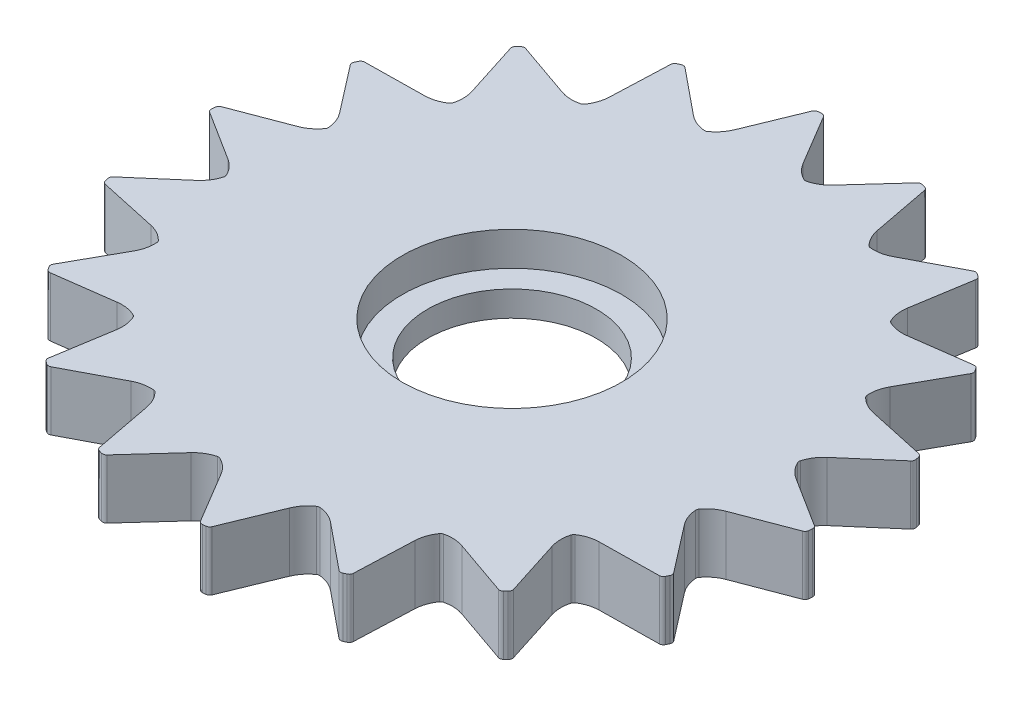
SolidWorks part; units mm, degrees
material "ASTM A36 Steel"
ref_plane "Front Plane" through (0, 0, 0) normal (0, 0, 1) x (1, 0, 0)
ref_plane "Top Plane" through (0, 0, 0) normal (0, 1, 0) x (1, 0, 0)
ref_plane "Right Plane" through (0, 0, 0) normal (1, 0, 0) x (0, 0, -1)
sketch "Sketch1" plane through (0, 0, 0) normal (0, 1, 0) x (1, 0, 0)
  line L0 (381.3467, 381.3133) -> (386.6619, 385.9057)
  line L1 (380.5553, 394.9141) -> (387.1206, 397.4117)
  line L2 (388.2042, 401.2572) -> (383.9089, 406.8152)
  line L3 (384.4633, 407.9654) -> (391.487, 408.0669)
  line L4 (393.8205, 411.3099) -> (391.6851, 418.0018)
  line L5 (392.5995, 418.893) -> (399.2343, 416.5861)
  line L6 (402.5362, 418.8354) -> (402.8184, 425.8541)
  line L7 (403.9825, 426.3788) -> (409.4282, 421.9419)
  line L8 (413.3003, 422.9262) -> (415.966, 429.4251)
  line L9 (417.2393, 429.52) -> (420.839, 423.4881)
  line L10 (424.8142, 423.0887) -> (429.5419, 428.2839)
  line L11 (430.7709, 427.9376) -> (432.0905, 421.0383)
  line L12 (435.6894, 419.3034) -> (441.9089, 422.5684)
  line L13 (442.9453, 421.8226) -> (441.8256, 414.888)
  line L14 (444.6141, 412.0268) -> (451.5752, 412.9677)
  line L15 (452.2941, 411.9125) -> (448.8701, 405.779)
  line L16 (450.5119, 402.1367) -> (457.3749, 400.64)
  line L17 (457.6895, 399.4025) -> (452.3743, 394.8101)
  line L18 (452.6713, 390.8259) -> (458.6086, 387.0721)
  line L19 (458.4809, 385.8017) -> (451.9156, 383.3041)
  line L20 (450.832, 379.4586) -> (455.1273, 373.9006)
  line L21 (454.5729, 372.7504) -> (447.5492, 372.6489)
  line L22 (445.2157, 369.4059) -> (447.3511, 362.714)
  line L23 (446.4367, 361.8228) -> (439.8019, 364.1297)
  line L24 (436.5, 361.8804) -> (436.2178, 354.8617)
  line L25 (435.0537, 354.337) -> (429.608, 358.774)
  line L26 (425.736, 357.7896) -> (423.0702, 351.2907)
  line L27 (421.7969, 351.1958) -> (418.1972, 357.2277)
  line L28 (414.222, 357.6271) -> (409.4943, 352.4319)
  line L29 (408.2653, 352.7782) -> (406.9457, 359.6775)
  line L30 (403.3468, 361.4124) -> (397.1273, 358.1474)
  line L31 (396.0909, 358.8932) -> (397.2106, 365.8278)
  line L32 (394.4221, 368.689) -> (387.461, 367.7481)
  line L33 (386.7421, 368.8033) -> (390.1661, 374.9368)
  line L34 (386.3649, 389.8899) -> (380.4276, 393.6437)
  line L35 (388.5244, 378.5791) -> (381.6613, 380.0758)
  arc A0 (390.5213, 377.4784) -> (388.5244, 378.5791) centre (387.6721, 374.6709) ccw
  arc A1 (381.2838, 380.4387) -> (381.6613, 380.0758) centre (381.7678, 380.5643) ccw
  arc A2 (381.1884, 380.8141) -> (381.2838, 380.4387) centre (419.5181, 390.3579) ccw
  arc A3 (381.3467, 381.3133) -> (381.1884, 380.8141) centre (381.6736, 380.9349) ccw
  arc A4 (386.6619, 385.9057) -> (387.8908, 387.8264) centre (384.0467, 388.9325) ccw
  arc A5 (387.8908, 387.8264) -> (387.865, 388.1726) centre (387.4103, 387.9647) ccw
  arc A6 (380.1971, 394.1138) -> (380.4276, 393.6437) centre (380.6948, 394.0663) ccw
  arc A7 (380.2358, 394.4992) -> (380.1971, 394.1138) centre (419.5181, 390.3579) ccw
  arc A8 (380.5553, 394.9141) -> (380.2358, 394.4992) centre (380.733, 394.4468) ccw
  arc A9 (387.1206, 397.4117) -> (388.9323, 398.7963) centre (385.6984, 401.1503) ccw
  arc A10 (388.9323, 398.7963) -> (389.0265, 399.1304) centre (388.5281, 399.0905) ccw
  arc A11 (389.0265, 399.1304) -> (388.2042, 401.2572) centre (385.0393, 398.8112) ccw
  arc A12 (383.853, 407.3359) -> (383.9089, 406.8152) centre (384.3045, 407.121) ccw
  arc A13 (384.0212, 407.6848) -> (383.853, 407.3359) centre (419.5181, 390.3579) ccw
  arc A14 (384.4633, 407.9654) -> (384.0212, 407.6848) centre (384.4706, 407.4655) ccw
  arc A15 (391.487, 408.0669) -> (393.663, 408.7483) centre (391.4292, 412.0665) ccw
  arc A16 (393.663, 408.7483) -> (393.8657, 409.0301) centre (393.3838, 409.1631) ccw
  arc A17 (393.8657, 409.0301) -> (393.8205, 411.3099) centre (390.0098, 410.0939) ccw
  arc A18 (391.8107, 418.5102) -> (391.6851, 418.0018) centre (392.1614, 418.1538) ccw
  arc A19 (392.0881, 418.7805) -> (391.8107, 418.5102) centre (419.5181, 390.3579) ccw
  arc A20 (392.5995, 418.893) -> (392.0881, 418.7805) centre (392.4353, 418.4207) ccw
  arc A21 (399.2343, 416.5861) -> (401.5121, 416.4822) centre (400.5479, 420.3643) ccw
  arc A22 (401.5121, 416.4822) -> (401.7991, 416.6777) centre (401.3916, 416.9675) ccw
  arc A23 (401.7991, 416.6777) -> (402.5362, 418.8354) centre (398.5395, 418.9961) ccw
  arc A24 (403.1103, 426.2889) -> (402.8184, 425.8541) centre (403.318, 425.834) ccw
  arc A25 (403.4634, 426.448) -> (403.1103, 426.2889) centre (419.5181, 390.3579) ccw
  arc A26 (403.9825, 426.3788) -> (403.4634, 426.448) centre (403.6667, 425.9912) ccw
  arc A27 (409.4282, 421.9419) -> (411.5331, 421.0651) centre (411.9548, 425.0429) ccw
  arc A28 (411.5331, 421.0651) -> (411.8695, 421.1507) centre (411.5858, 421.5624) ccw
  arc A29 (411.8695, 421.1507) -> (413.3003, 422.9262) centre (409.5995, 424.4441) ccw
  arc A30 (416.3889, 429.7338) -> (415.966, 429.4251) centre (416.4286, 429.2353) ccw
  arc A31 (416.7752, 429.7626) -> (416.3889, 429.7338) centre (419.5181, 390.3579) ccw
  arc A32 (417.2393, 429.52) -> (416.7752, 429.7626) centre (416.8099, 429.2638) ccw
  arc A33 (420.839, 423.4881) -> (422.5171, 421.9443) centre (424.2738, 425.5379) ccw
  arc A34 (422.5171, 421.9443) -> (422.8626, 421.9096) centre (422.7367, 422.3935) ccw
  arc A35 (422.8626, 421.9096) -> (424.8142, 423.0887) centre (421.8558, 425.7808) ccw
  arc A36 (430.045, 428.4293) -> (429.5419, 428.2839) centre (429.9117, 427.9474) ccw
  arc A37 (430.4178, 428.3243) -> (430.045, 428.4293) centre (419.5181, 390.3579) ccw
  arc A38 (430.7709, 427.9376) -> (430.4178, 428.3243) centre (430.2798, 427.8437) ccw
  arc A39 (432.0905, 421.0383) -> (433.1394, 419.0137) centre (436.0193, 421.7897) ccw
  arc A40 (433.1394, 419.0137) -> (433.4522, 418.8629) centre (433.4994, 419.3607) ccw
  arc A41 (433.4522, 418.8629) -> (435.6894, 419.3034) centre (433.8302, 422.845) ccw
  arc A42 (442.4313, 422.5329) -> (441.9089, 422.5684) centre (442.1413, 422.1257) ccw
  arc A43 (442.7457, 422.3067) -> (442.4313, 422.5329) centre (419.5181, 390.3579) ccw
  arc A44 (442.9453, 421.8226) -> (442.7457, 422.3067) centre (442.4517, 421.9023) ccw
  arc A45 (441.8256, 414.888) -> (442.1188, 412.6268) centre (445.7745, 414.2504) ccw
  arc A46 (442.1188, 412.6268) -> (442.3611, 412.3781) centre (442.5758, 412.8297) ccw
  arc A47 (442.3611, 412.3781) -> (444.6141, 412.0268) centre (444.0783, 415.9908) ccw
  arc A48 (452.054, 412.7558) -> (451.5752, 412.9677) centre (451.6422, 412.4722) ccw
  arc A49 (452.2721, 412.4356) -> (452.054, 412.7558) centre (419.5181, 390.3579) ccw
  arc A50 (452.2941, 411.9125) -> (452.2721, 412.4356) centre (451.8575, 412.1562) ccw
  arc A51 (448.8701, 405.779) -> (448.3722, 403.5539) centre (452.3628, 403.8293) ccw
  arc A52 (448.3722, 403.5539) -> (448.5149, 403.2374) centre (448.8711, 403.5883) ccw
  arc A53 (448.5149, 403.2374) -> (450.5119, 402.1367) centre (451.3641, 406.0449) ccw
  arc A54 (457.7524, 400.2771) -> (457.3749, 400.64) centre (457.2684, 400.1515) ccw
  arc A55 (457.8478, 399.9017) -> (457.7524, 400.2771) centre (419.5181, 390.3579) ccw
  arc A56 (457.6895, 399.4025) -> (457.8478, 399.9017) centre (457.3626, 399.7809) ccw
  arc A57 (452.3743, 394.8101) -> (451.1454, 392.8894) centre (454.9895, 391.7833) ccw
  arc A58 (451.1454, 392.8894) -> (451.1712, 392.5432) centre (451.6259, 392.7511) ccw
  arc A59 (451.1712, 392.5432) -> (452.6713, 390.8259) centre (454.8088, 394.2068) ccw
  arc A60 (458.8391, 386.602) -> (458.6086, 387.0721) centre (458.3414, 386.6495) ccw
  arc A61 (458.8004, 386.2166) -> (458.8391, 386.602) centre (419.5181, 390.3579) ccw
  arc A62 (458.4809, 385.8017) -> (458.8004, 386.2166) centre (458.3032, 386.269) ccw
  arc A63 (451.9156, 383.3041) -> (450.1039, 381.9195) centre (453.3378, 379.5655) ccw
  arc A64 (450.1039, 381.9195) -> (450.0097, 381.5854) centre (450.5081, 381.6253) ccw
  arc A65 (450.0097, 381.5854) -> (450.832, 379.4586) centre (453.997, 381.9046) ccw
  arc A66 (455.1832, 373.3799) -> (455.1273, 373.9006) centre (454.7317, 373.5948) ccw
  arc A67 (455.015, 373.031) -> (455.1832, 373.3799) centre (419.5181, 390.3579) ccw
  arc A68 (454.5729, 372.7504) -> (455.015, 373.031) centre (454.5656, 373.2503) ccw
  arc A69 (447.5492, 372.6489) -> (445.3732, 371.9675) centre (447.607, 368.6493) ccw
  arc A70 (445.3732, 371.9675) -> (445.1705, 371.6857) centre (445.6525, 371.5527) ccw
  arc A71 (445.1705, 371.6857) -> (445.2157, 369.4059) centre (449.0264, 370.6219) ccw
  arc A72 (447.2255, 362.2056) -> (447.3511, 362.714) centre (446.8748, 362.562) ccw
  arc A73 (446.9481, 361.9353) -> (447.2255, 362.2056) centre (419.5181, 390.3579) ccw
  arc A74 (446.4367, 361.8228) -> (446.9481, 361.9353) centre (446.6009, 362.2951) ccw
  arc A75 (439.8019, 364.1297) -> (437.5241, 364.2336) centre (438.4883, 360.3515) ccw
  arc A76 (437.5241, 364.2336) -> (437.2371, 364.0381) centre (437.6446, 363.7483) ccw
  arc A77 (437.2371, 364.0381) -> (436.5, 361.8804) centre (440.4967, 361.7197) ccw
  arc A78 (435.9259, 354.4269) -> (436.2178, 354.8617) centre (435.7182, 354.8818) ccw
  arc A79 (435.5728, 354.2678) -> (435.9259, 354.4269) centre (419.5181, 390.3579) ccw
  arc A80 (435.0537, 354.337) -> (435.5728, 354.2678) centre (435.3695, 354.7246) ccw
  arc A81 (429.608, 358.774) -> (427.5031, 359.6507) centre (427.0814, 355.6729) ccw
  arc A82 (427.5031, 359.6507) -> (427.1667, 359.5651) centre (427.4504, 359.1534) ccw
  arc A83 (427.1667, 359.5651) -> (425.736, 357.7896) centre (429.4367, 356.2717) ccw
  arc A84 (422.6473, 350.982) -> (423.0702, 351.2907) centre (422.6076, 351.4805) ccw
  arc A85 (422.261, 350.9532) -> (422.6473, 350.982) centre (419.5181, 390.3579) ccw
  arc A86 (421.7969, 351.1958) -> (422.261, 350.9532) centre (422.2263, 351.452) ccw
  arc A87 (418.1972, 357.2277) -> (416.5191, 358.7715) centre (414.7624, 355.1779) ccw
  arc A88 (416.5191, 358.7715) -> (416.1736, 358.8062) centre (416.2995, 358.3223) ccw
  arc A89 (416.1736, 358.8062) -> (414.222, 357.6271) centre (417.1804, 354.935) ccw
  arc A90 (408.9912, 352.2865) -> (409.4943, 352.4319) centre (409.1245, 352.7684) ccw
  arc A91 (408.6184, 352.3915) -> (408.9912, 352.2865) centre (419.5181, 390.3579) ccw
  arc A92 (408.2653, 352.7782) -> (408.6184, 352.3915) centre (408.7564, 352.8721) ccw
  arc A93 (406.9457, 359.6775) -> (405.8968, 361.7021) centre (403.0169, 358.9261) ccw
  arc A94 (405.8968, 361.7021) -> (405.584, 361.8529) centre (405.5368, 361.3551) ccw
  arc A95 (405.584, 361.8529) -> (403.3468, 361.4124) centre (405.206, 357.8708) ccw
  arc A96 (396.6049, 358.1829) -> (397.1273, 358.1474) centre (396.8949, 358.5901) ccw
  arc A97 (396.2905, 358.4091) -> (396.6049, 358.1829) centre (419.5181, 390.3579) ccw
  arc A98 (396.0909, 358.8932) -> (396.2905, 358.4091) centre (396.5845, 358.8135) ccw
  arc A99 (397.2106, 365.8278) -> (396.9174, 368.089) centre (393.2617, 366.4654) ccw
  arc A100 (396.9174, 368.089) -> (396.6751, 368.3377) centre (396.4604, 367.8861) ccw
  arc A101 (396.6751, 368.3377) -> (394.4221, 368.689) centre (394.9579, 364.725) ccw
  arc A102 (386.9822, 367.96) -> (387.461, 367.7481) centre (387.394, 368.2436) ccw
  arc A103 (390.1661, 374.9368) -> (390.664, 377.1619) centre (386.6734, 376.8865) ccw
  arc A104 (390.664, 377.1619) -> (390.5213, 377.4784) centre (390.1651, 377.1275) ccw
  arc A105 (387.865, 388.1726) -> (386.3649, 389.8899) centre (384.2274, 386.509) ccw
  arc A106 (386.7641, 368.2802) -> (386.9822, 367.96) centre (419.5181, 390.3579) ccw
  arc A107 (386.7421, 368.8033) -> (386.7641, 368.2802) centre (387.1787, 368.5596) ccw
  circle A108 centre (419.5181, 390.3579) radius 10
extrude "Boss-Extrude1" add sketch "Sketch1" along normal blind 7
sketch "Sketch2" plane through (0, 7, 0) normal (0, 1, 0) x (1, 0, 0)
  circle A0 centre (419.5181, 390.3579) radius 13
  dimension "D1" = 26
extrude "Cut-Extrude1" cut sketch "Sketch2" against normal blind 4
